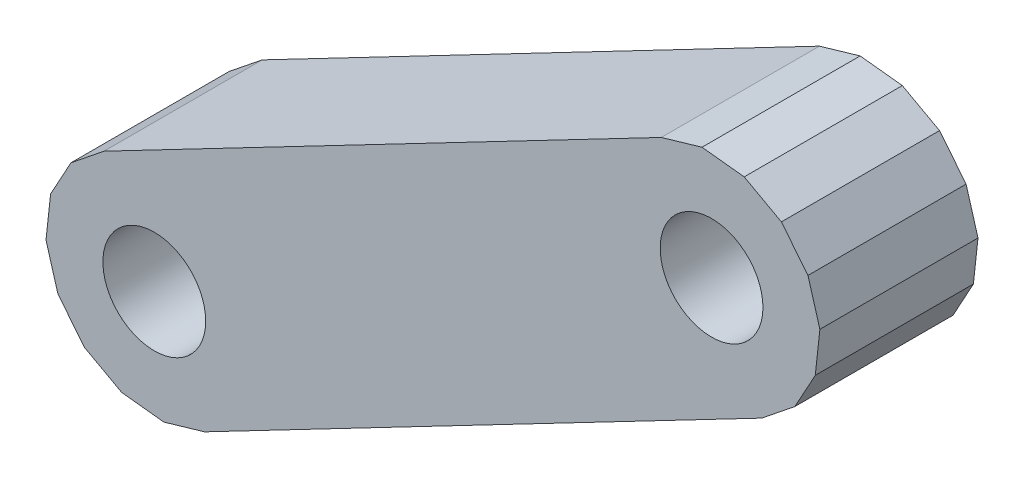
SolidWorks part; units mm, degrees
ref_plane "前视基准面" through (0, 0, 0) normal (0, 0, 1) x (1, 0, 0)
ref_plane "上视基准面" through (0, 0, 0) normal (0, 1, 0) x (1, 0, 0)
ref_plane "右视基准面" through (0, 0, 0) normal (1, 0, 0) x (0, 0, -1)
other "Configuration Table"
sketch "草图1" plane through (0, 0, 0) normal (0, 0, 1) x (1, 0, 0)
  line L0 (43.7332, 35.82) -> (45.406, 37.1642)
  line L1 (45.406, 37.1642) -> (46.4371, 39.0463)
  line L2 (46.4371, 39.0463) -> (46.6694, 41.1797)
  line L3 (46.6694, 41.1797) -> (46.0676, 43.2396)
  line L4 (46.0676, 43.2396) -> (44.7234, 44.9124)
  line L5 (44.7234, 44.9124) -> (42.8413, 45.9434)
  line L6 (42.8413, 45.9434) -> (40.7079, 46.1757)
  line L7 (40.7079, 46.1757) -> (38.648, 45.574)
  line L8 (38.648, 45.574) -> (10.4574, 30.877)
  line L9 (10.4574, 30.877) -> (8.7846, 29.5328)
  line L10 (8.7846, 29.5328) -> (7.7535, 27.6507)
  line L11 (7.7535, 27.6507) -> (7.5212, 25.5173)
  line L12 (7.5212, 25.5173) -> (8.123, 23.4574)
  line L13 (8.123, 23.4574) -> (9.4672, 21.7846)
  line L14 (9.4672, 21.7846) -> (11.3493, 20.7535)
  line L15 (11.3493, 20.7535) -> (13.4827, 20.5212)
  line L16 (13.4827, 20.5212) -> (15.5426, 21.123)
  line L17 (15.5426, 21.123) -> (43.7332, 35.82)
  dimension "x0" = 43.7332
  dimension "x1" = 45.406
  dimension "x2" = 46.4371
  dimension "x3" = 46.6694
  dimension "x4" = 46.0676
  dimension "x5" = 44.7234
  dimension "x6" = 42.8413
  dimension "x7" = 40.7079
  dimension "x8" = 38.648
  dimension "x9" = 10.4574
  dimension "x10" = 8.7846
  dimension "x11" = 7.7535
  dimension "x12" = 7.5212
  dimension "x13" = 8.123
  dimension "x14" = 9.4672
  dimension "x15" = 11.3493
  dimension "x16" = 13.4827
  dimension "x17" = 15.5426
  dimension "y0" = 35.82
  dimension "y1" = 37.1642
  dimension "y2" = 39.0463
  dimension "y3" = 41.1797
  dimension "y4" = 43.2396
  dimension "y5" = 44.9124
  dimension "y6" = 45.9434
  dimension "y7" = 46.1757
  dimension "y8" = 45.574
  dimension "y9" = 30.877
  dimension "y10" = 29.5328
  dimension "y11" = 27.6507
  dimension "y12" = 25.5173
  dimension "y13" = 23.4574
  dimension "y14" = 21.7846
  dimension "y15" = 20.7535
  dimension "y16" = 20.5212
  dimension "y17" = 21.123
extrude "High_slider_link" add sketch "草图1" along normal blind 8
sketch "草图2" plane through (0, 0, 8) normal (0, 0, 1) x (1, 0, 0)
  circle A0 centre (41.1906, 40.697) radius 2.6
  dimension "diameter" = 5.2
  dimension "x" = 41.1906
  dimension "y" = 40.697
extrude "Pin_bore" cut sketch "草图2" against normal through all
sketch "草图3" plane through (0, 0, 8) normal (0, 0, 1) x (1, 0, 0)
  circle A0 centre (13, 26) radius 2.6
  dimension "diameter" = 5.2
  dimension "x" = 13
  dimension "y" = 26
extrude "切除-拉伸2" cut sketch "草图3" against normal through all
